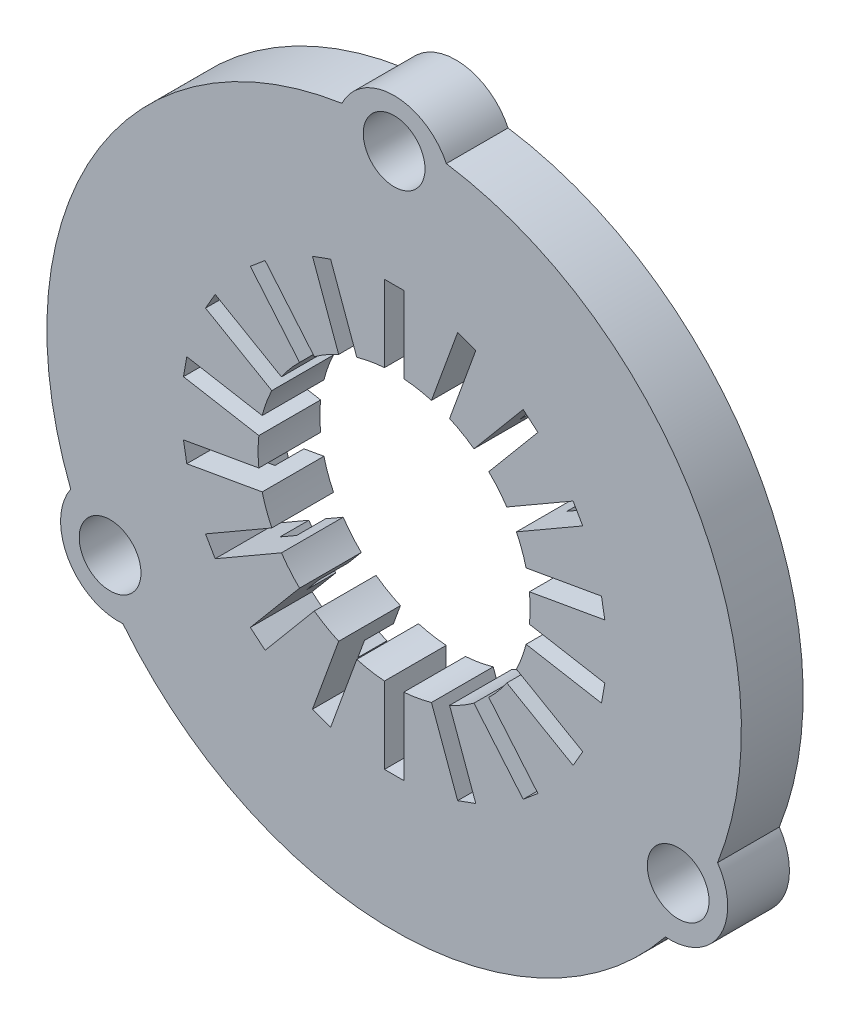
SolidWorks part; units mm, degrees
ref_plane "前视基准面" through (0, 0, 0) normal (0, 0, 1) x (1, 0, 0)
ref_plane "上视基准面" through (0, 0, 0) normal (0, 1, 0) x (1, 0, 0)
ref_plane "右视基准面" through (0, 0, 0) normal (1, 0, 0) x (0, 0, -1)
sketch "草图1" plane through (0, 0, 0) normal (0, 0, 1) x (1, 0, 0)
  circle A0 centre (0, 0) radius 7.05
  arc A1 (-14.0584, -11.2411) -> (14.0584, -11.2411) centre (0, 0) ccw
  circle A2 centre (0, 0) radius 16.5 construction
  arc A3 (2.7059, 17.7955) -> (-2.7059, 17.7955) centre (0, 16.5) ccw
  arc A4 (14.0584, -11.2411) -> (16.7643, -6.5544) centre (14.2894, -8.25) ccw
  arc A5 (-16.7643, -6.5544) -> (-14.0584, -11.2411) centre (-14.2894, -8.25) ccw
  arc A6 (16.7643, -6.5544) -> (2.7059, 17.7955) centre (0, 0) ccw
  arc A7 (-2.7059, 17.7955) -> (-16.7643, -6.5544) centre (0, 0) ccw
  point P14 (0, 0)
  dimension "D1" = 3
extrude "凸台-拉伸1" add sketch "草图1" along normal blind 3.2
sketch "草图2" plane through (0, 0, 3.2) normal (0, 0, 1) x (1, 0, 0)
  circle A0 centre (0, 0) radius 17 construction
  circle A1 centre (0, 17) radius 1.6
  circle A2 centre (14.7224, -8.5) radius 1.6
  circle A3 centre (-14.7224, -8.5) radius 1.6
  point P12 (0, 0)
extrude "切除-拉伸1" cut sketch "草图2" against normal blind 10
sketch "草图3" plane through (0, 0, 0) normal (0, 0, -1) x (-1, 0, 0)
  line L0 (0, 0) -> (0.5, 0)
  line L1 (0.5, 0) -> (0.5, 11)
  line L2 (0.5, 11) -> (-0.5, 11)
  line L3 (-0.5, 11) -> (-0.5, 0)
  circle M14 centre (0, 0) radius 7.05
extrude "切除-拉伸3" cut sketch "草图3" against normal blind 4 and the other way through all contours L2 L3 L1 M14
pattern_circular "阵列(圆周)1" count 18 over 360 about axis through (0, 0, 0) along (0, 0, 1) of "切除-拉伸3"
sketch "草图4" plane through (0, 0, 0) normal (0, 0, -1) x (-1, 0, 0)
  circle A0 centre (0, 0) radius 9.1
  circle A1 centre (0, 0) radius 8.1
extrude "切除-拉伸4" cut sketch "草图4" against normal blind 1.5
